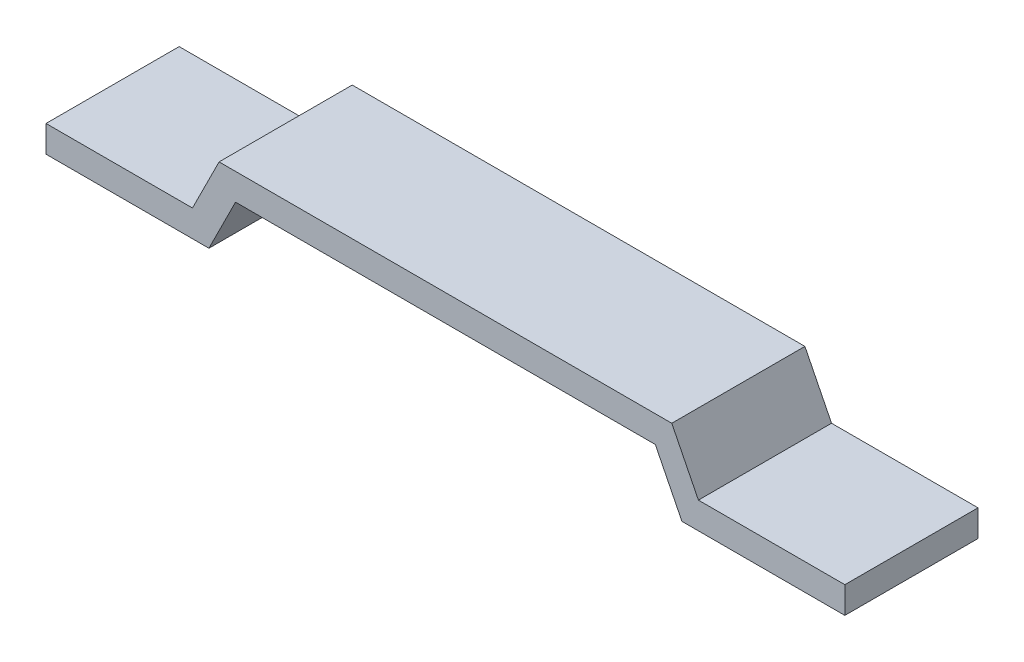
SolidWorks part; units mm, degrees
ref_plane "Front Plane" through (0, 0, 0) normal (0, 0, 1) x (1, 0, 0)
ref_plane "Top Plane" through (0, 0, 0) normal (0, 1, 0) x (1, 0, 0)
ref_plane "Right Plane" through (0, 0, 0) normal (1, 0, 0) x (0, 0, -1)
sketch "Sketch1" plane through (0, 0, 0) normal (0, 0, 1) x (1, 0, 0)
  line L0 (-150, 0) -> (-150, 10)
  line L1 (-150, 10) -> (-95, 10)
  line L2 (-95, 10) -> (-85, 30)
  line L3 (-85, 30) -> (0, 30)
  line L4 (-140, 0) -> (-150, 0)
  line L5 (-140, 0) -> (-88.8197, 0)
  line L6 (-88.8197, 0) -> (-78.8197, 20)
  line L7 (-78.8197, 20) -> (0, 20)
  line L8 (-140, 0) -> (-140, 0) construction
  line L9 (-150, 0) -> (-150, 10) construction
  line L10 (0, 52.2145) -> (0, -21.9982) construction
  line L11 (78.8197, 20) -> (0, 20)
  line L12 (88.8197, 0) -> (78.8197, 20)
  line L13 (140, 0) -> (88.8197, 0)
  line L14 (140, 0) -> (150, 0)
  line L15 (85, 30) -> (0, 30)
  line L16 (95, 10) -> (85, 30)
  line L17 (150, 10) -> (95, 10)
  line L18 (150, 0) -> (150, 10)
  dimension "D2" = 0
  dimension "D3" = 85
  dimension "D4" = 150
  dimension "D5" = 30
  dimension "D6" = 55
  dimension "D1" = 10
extrude "Boss-Extrude1" add sketch "Sketch1" along normal blind 50
